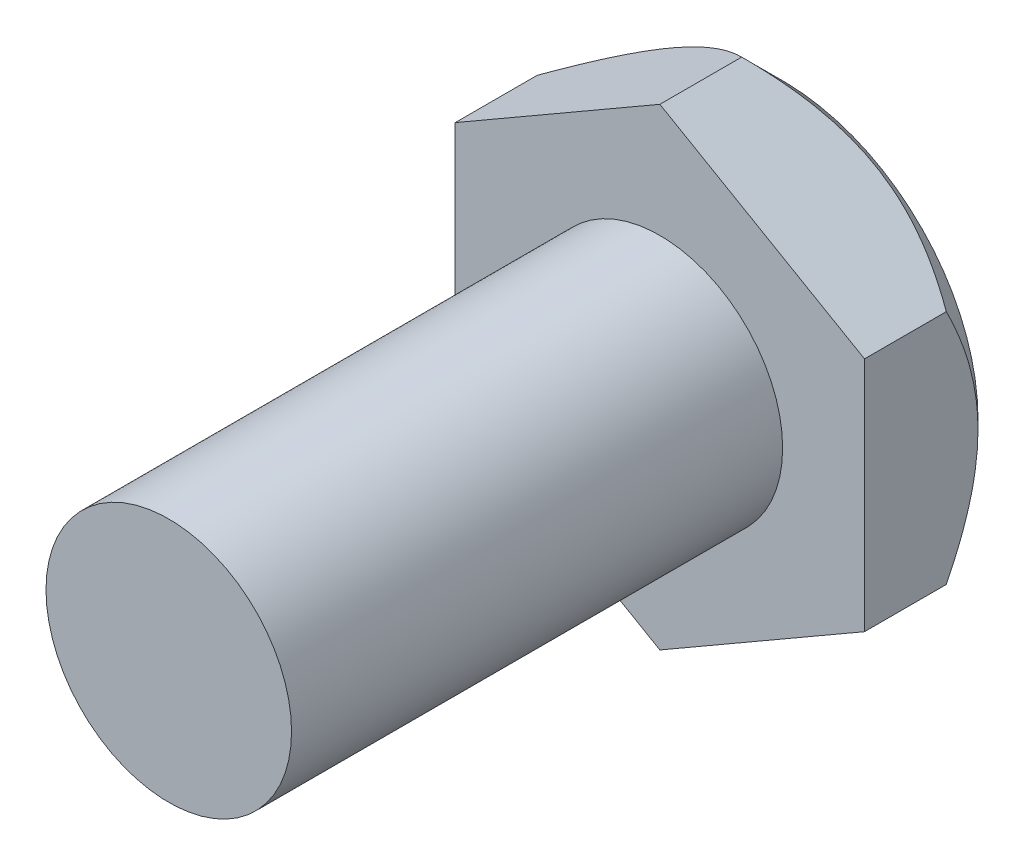
SolidWorks part; units mm, degrees
material "AISI 1020"
ref_plane "Front Plane" through (0, 0, 0) normal (0, 0, 1) x (1, 0, 0)
ref_plane "Top Plane" through (0, 0, 0) normal (0, 1, 0) x (1, 0, 0)
ref_plane "Right Plane" through (0, 0, 0) normal (1, 0, 0) x (0, 0, -1)
sketch "Sketch1" plane through (0, 0, 0) normal (0, 0, 1) x (1, 0, 0)
  line L1 (0, -5.7735) -> (5, -2.8868)
  line L2 (5, -2.8868) -> (5, 2.8868)
  line L3 (5, 2.8868) -> (0, 5.7735)
  line L4 (0, 5.7735) -> (-5, 2.8868)
  line L5 (-5, 2.8868) -> (-5, -2.8868)
  line L6 (-5, -2.8868) -> (0, -5.7735)
  circle A0 centre (0, 0) radius 5 construction
  dimension "D1" = 10
extrude "Boss-Extrude1" add sketch "Sketch1" along normal blind 3
sketch "Sketch2" plane through (0, 0, 3) normal (0, 0, 1) x (1, 0, 0)
  circle A0 centre (0, 0) radius 3
  dimension "D1" = 6
extrude "Boss-Extrude2" add sketch "Sketch2" along normal blind 12
cosmetic thread "Cosmetic Thread1" parameters "D1"=10, "D2"=4.891
sketch "Sketch3" plane through (0, 0, 0) normal (1, 0, 0) x (0, 0, -1)
  line L0 (-1, 5.7735) -> (0, 5.7735)
  line L1 (-3, 5.7735) -> (0, 5.7735) construction
  line L2 (0, 5.7735) -> (0, 4.7735)
  line L3 (0, 2.8868) -> (0, 5.7735) construction
  line L4 (0, 4.7735) -> (-1, 5.7735)
  line L5 (-11.1685, 0) -> (4.2338, 0) construction
  dimension "D1" = 1
  dimension "D2" = 1
revolve "Cut-Revolve1" cut sketch "Sketch3" angle 360 about L5
